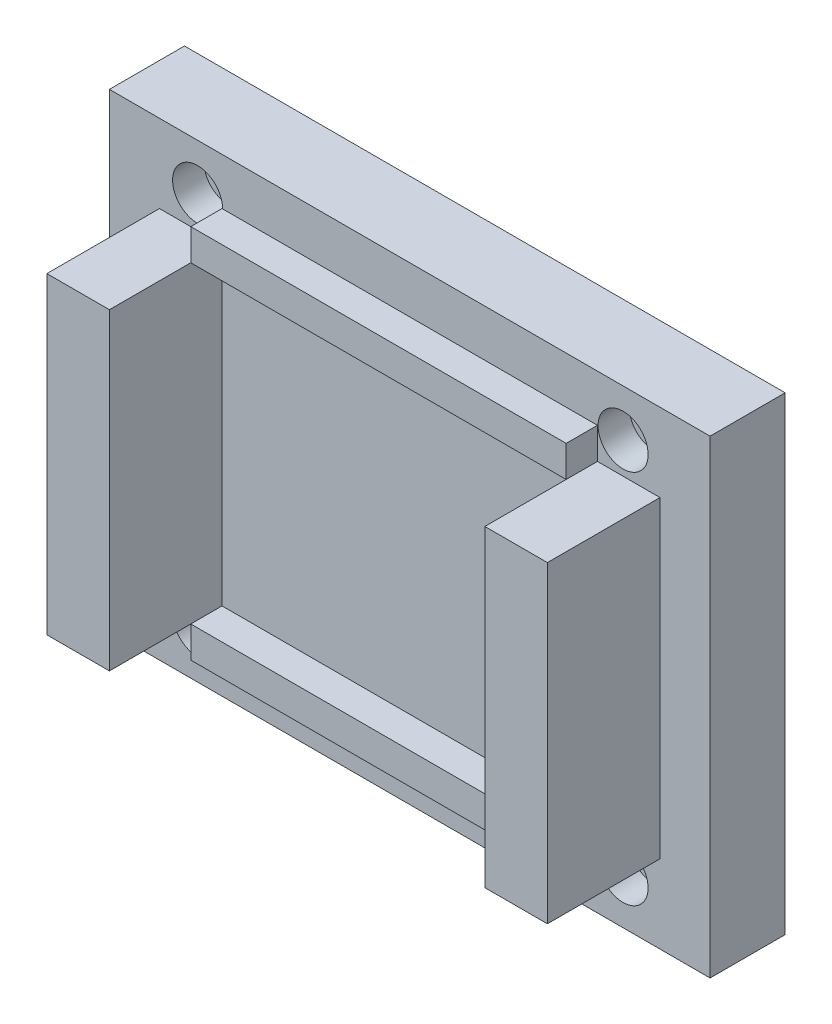
SolidWorks part; units mm, degrees
ref_plane "정면" through (0, 0, 0) normal (0, 0, 1) x (1, 0, 0)
ref_plane "윗면" through (0, 0, 0) normal (0, 1, 0) x (1, 0, 0)
ref_plane "우측면" through (0, 0, 0) normal (1, 0, 0) x (0, 0, -1)
sketch "스케치1" plane through (0, 0, 0) normal (0, 0, 1) x (1, 0, 0)
  line L1 (0, 0) -> (96, 0)
  line L2 (0, 0) -> (0, 75)
  line L3 (0, 75) -> (96, 75)
  line L4 (96, 0) -> (96, 75)
  dimension "D1" = 75
  dimension "D2" = 96
extrude "보스-돌출1" add sketch "스케치1" along normal blind 12
sketch "스케치2" plane through (0, 0, 12) normal (0, 0, 1) x (1, 0, 0)
  line L1 (0, 0) -> (96, 0) construction
  line L3 (96, 0) -> (96, 75) construction
  line L4 (96, 75) -> (0, 75) construction
  circle A0 centre (14.0956, 67.5) radius 4
  circle A1 centre (82.0956, 67.5) radius 4
  circle A2 centre (82.0956, 7.5) radius 4
  circle A3 centre (14.0956, 7.5) radius 4
  dimension "D1" = 8
  dimension "D2" = 68
  dimension "D3" = 60
  dimension "D4" = 7.5
  dimension "D5" = 14.0956
  dimension "D6" = 13.9044
  dimension "D7" = 7.5
extrude "컷-돌출1" cut sketch "스케치2" against normal blind 5
sketch "스케치3" plane through (0, 0, 12) normal (0, 0, 1) x (1, 0, 0)
  circle A0 centre (14.0956, 67.5) radius 2.5
  circle A1 centre (82.0956, 67.5) radius 2.5
  circle A2 centre (82.0956, 7.5) radius 2.5
  circle A3 centre (14.0956, 7.5) radius 2.5
  dimension "D1" = 5
extrude "컷-돌출2" cut sketch "스케치3" against normal through all
sketch "스케치4" plane through (0, 0, 12) normal (0, 0, 1) x (1, 0, 0)
  line L10 (0, 75) -> (0, 0) construction
  line L19 (18, 12.5) -> (78, 12.5)
  line L20 (18, 12.5) -> (18, 62.5)
  line L21 (18, 62.5) -> (78, 62.5)
  line L22 (78, 12.5) -> (78, 62.5)
  line L23 (0, 0) -> (96, 0) construction
  line L26 (18, 62.5) -> (8, 62.5)
  line L27 (18, 62.5) -> (18, 12.5)
  line L28 (18, 12.5) -> (8, 12.5)
  line L29 (8, 62.5) -> (8, 12.5)
  line L30 (78, 62.5) -> (88, 62.5)
  line L31 (78, 62.5) -> (78, 12.5)
  line L32 (78, 12.5) -> (88, 12.5)
  line L33 (88, 62.5) -> (88, 12.5)
  line L34 (18, 62.5) -> (78, 62.5)
  line L35 (18, 62.5) -> (18, 67.5)
  line L36 (18, 67.5) -> (78, 67.5)
  line L37 (78, 62.5) -> (78, 67.5)
  line L38 (18, 12.5) -> (78, 12.5)
  line L39 (18, 12.5) -> (18, 7.5)
  line L40 (18, 7.5) -> (78, 7.5)
  line L41 (78, 12.5) -> (78, 7.5)
  dimension "D1" = 60
  dimension "D2" = 50
  dimension "D3" = 18
  dimension "D4" = 12.5
  dimension "D5" = 10
  dimension "D6" = 10
  dimension "D7" = 5
  dimension "D8" = 5
extrude "보스-돌출2" add sketch "스케치4" along normal blind 18 contours L26 L29 L28 L20 | L33 L30 L22 L32
sketch "스케치5" plane through (0, 0, 12) normal (0, 0, 1) x (1, 0, 0)
  line L0 (18, 62.5) -> (78, 62.5)
  line L9 (18, 62.5) -> (18, 67.5)
  line L10 (78, 62.5) -> (78, 67.5)
  line L11 (18, 67.5) -> (78, 67.5)
  dimension "D1" = 5
extrude "보스-돌출7" add sketch "스케치5" along normal blind 5 separate body contours L0 L9 L11 L10
sketch "스케치6" plane through (0, 0, 12) normal (0, 0, 1) x (1, 0, 0)
  line L0 (18, 12.5) -> (78, 12.5)
  line L1 (18, 12.5) -> (18, 7.5)
  line L2 (78, 12.5) -> (78, 7.5)
  line L3 (18, 7.5) -> (78, 7.5)
  dimension "D1" = 5
extrude "보스-돌출8" add sketch "스케치6" along normal blind 5 separate body
